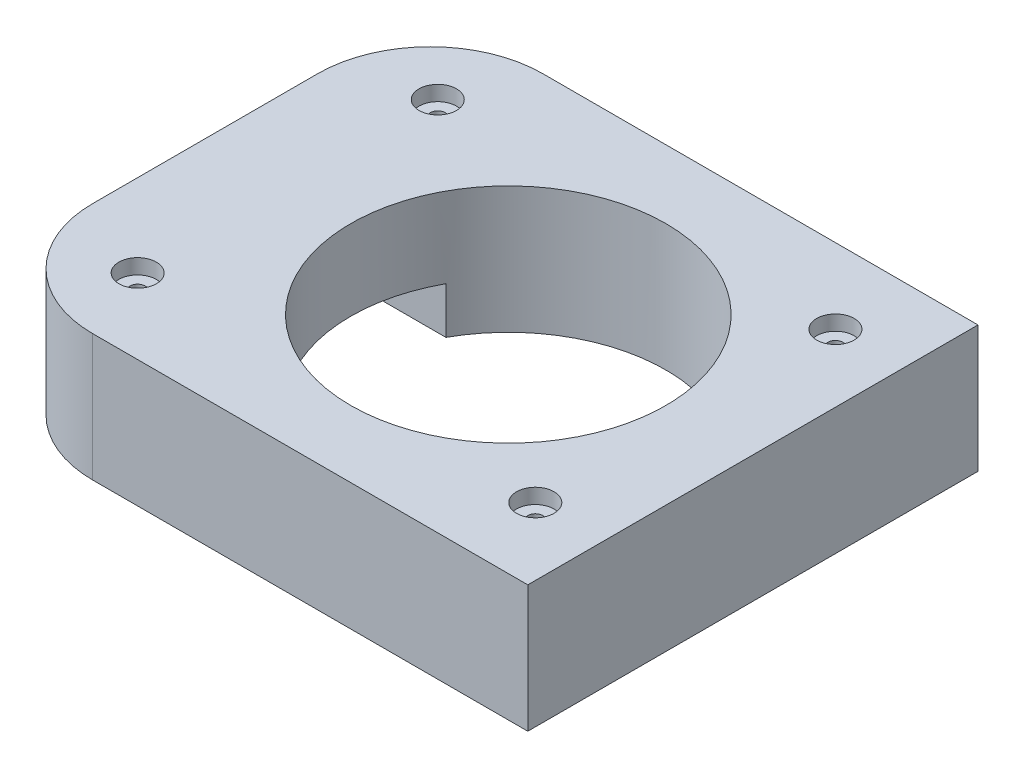
SolidWorks part; units mm, degrees
ref_plane "Front Plane" through (0, 0, 0) normal (0, 0, 1) x (1, 0, 0)
ref_plane "Top Plane" through (0, 0, 0) normal (0, 1, 0) x (1, 0, 0)
ref_plane "Right Plane" through (0, 0, 0) normal (1, 0, 0) x (0, 0, -1)
sketch "Sketch1" plane through (0, 0, 0) normal (0, 1, 0) x (1, 0, 0)
  line L1 (43, 30) -> (-30, 30)
  line L3 (43, -30) -> (-30, -30)
  line L4 (-30, 30) -> (-30, -30)
  line L6 (43, 30) -> (43, -30)
  point P0 (0, 0)
extrude "Boss-Extrude1" add sketch "Sketch1" along normal blind 16.9
fillet "Fillet1" radius 15 2 edges at (-30, 8.45, -30) (-30, 8.45, 30)
sketch "Sketch2" plane through (0, 16.9, 0) normal (0, 1, 0) x (1, 0, 0)
  circle A0 centre (10.5, -0.1) radius 21
extrude "Cut-Extrude1" cut sketch "Sketch2" against normal up to next
sketch "Sketch3" plane through (0, 0, 0) normal (0, -1, 0) x (1, 0, 0)
  line L0 (-30, -15) -> (-30, 15) construction
  line L1 (-30, -10) -> (10, -10)
  line L2 (-30, -10) -> (-30, 10)
  line L3 (-30, 10) -> (10, 10)
  line L4 (10, -10) -> (10, 10)
  line L5 (-20.5, -10) -> (-30, -10) construction
extrude "Cut-Extrude2" cut sketch "Sketch3" against normal blind 6.2
sketch "Sketch4" plane through (0, 16.9, 0) normal (0, 1, 0) x (1, 0, 0)
  line L0 (43, 30) -> (-15, 30) construction
  line L1 (34, 20) -> (-19, 20) construction
  line L2 (34, 20) -> (34, -20) construction
  line L3 (34, -20) -> (-19, -20) construction
  line L4 (-19, 20) -> (-19, -20) construction
  line L5 (-15, -30) -> (43, -30) construction
  line L6 (-30, 15) -> (-30, -15) construction
  line L7 (43, -30) -> (43, 30) construction
  circle A0 centre (34, 20) radius 1
  circle A1 centre (34, -20) radius 1
  circle A2 centre (-19, -20) radius 1
  circle A3 centre (-19, 20) radius 1
  dimension "D1" = 10
  dimension "D2" = 10
  dimension "D3" = 11
  dimension "D4" = 9
extrude "Cut-Extrude3" cut sketch "Sketch4" against normal up to next
sketch "Sketch5" plane through (0, 16.9, 0) normal (0, 1, 0) x (1, 0, 0)
  circle A0 centre (-19, 20) radius 2.5
  circle A1 centre (-19, -20) radius 2.5
  circle A2 centre (34, -20) radius 2.5
  circle A3 centre (34, 20) radius 2.5
extrude "Cut-Extrude4" cut sketch "Sketch5" against normal blind 2
